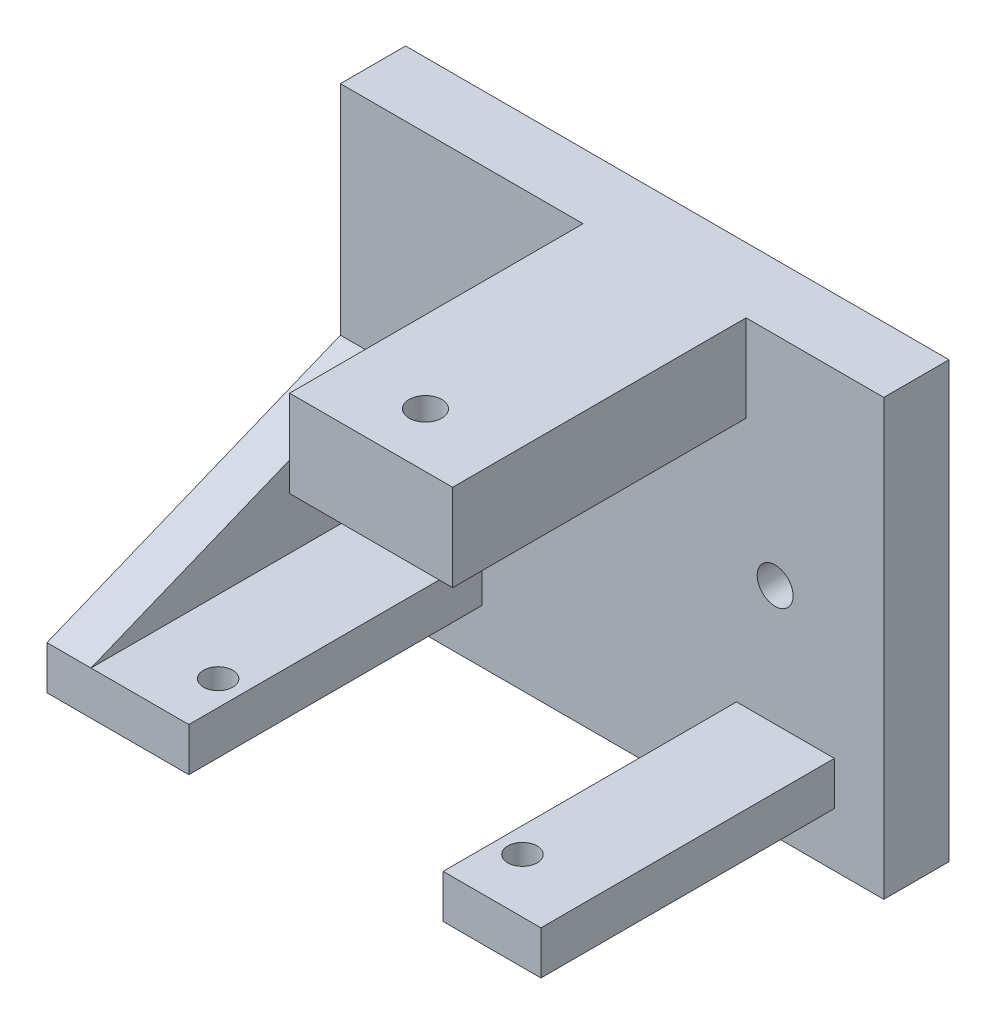
SolidWorks part; units mm, degrees
ref_plane "前视基准面" through (0, 0, 0) normal (0, 0, 1) x (1, 0, 0)
ref_plane "上视基准面" through (0, 0, 0) normal (0, 1, 0) x (1, 0, 0)
ref_plane "右视基准面" through (0, 0, 0) normal (1, 0, 0) x (0, 0, -1)
sketch "草图1" plane through (0, 0, 0) normal (0, 0, 1) x (1, 0, 0)
  line L0 (219.1261, 0) -> (249.1261, 0) construction
  line L2 (209.1261, 20) -> (259.1261, 20)
  line L3 (209.1261, 20) -> (209.1261, -20)
  line L4 (209.1261, -20) -> (259.1261, -20)
  line L5 (259.1261, 20) -> (259.1261, -20)
  line L6 (209.1261, 20) -> (259.1261, -20) construction
  line L7 (209.1261, -20) -> (259.1261, 20) construction
  circle A0 centre (219.1261, 0) radius 1.65
  circle A1 centre (249.1261, 0) radius 1.65
  point P4 (234.1261, 0)
  dimension "D4" = 3.3
  dimension "D1" = 10
  dimension "D2" = 50
  dimension "D3" = 40
extrude "凸台-拉伸1" add sketch "草图1" along normal blind 6
sketch "草图4" plane through (0, 0, 6) normal (0, 0, 1) x (1, 0, 0)
  line L0 (233.8761, 20) -> (233.8761, -20) construction
  line L3 (206.4014, -13.0416) -> (265.494, -13.0416) construction
  line L4 (222.6261, -15.0416) -> (217.7011, -15.0416) construction
  line L5 (213.1761, -11.0416) -> (222.1761, -11.0416)
  line L6 (213.1761, -11.0416) -> (213.1761, -15.0416)
  line L7 (213.1761, -15.0416) -> (222.1761, -15.0416)
  line L8 (222.1761, -11.0416) -> (222.1761, -15.0416)
  line L9 (213.1761, -11.0416) -> (222.1761, -15.0416) construction
  line L10 (213.1761, -15.0416) -> (222.1761, -11.0416) construction
  line L11 (254.5761, -15.0416) -> (245.5761, -11.0416) construction
  line L12 (254.5761, -11.0416) -> (245.5761, -15.0416) construction
  line L13 (245.5761, -11.0416) -> (245.5761, -15.0416)
  line L14 (254.5761, -15.0416) -> (245.5761, -15.0416)
  line L15 (254.5761, -11.0416) -> (254.5761, -15.0416)
  line L16 (254.5761, -11.0416) -> (245.5761, -11.0416)
  line L19 (259.1261, -20) -> (259.1261, 20) construction
  point P8 (217.6761, -13.0416)
  point P19 (250.0761, -13.0416)
  dimension "D1" = 4
  dimension "D2" = 9
  dimension "D3" = 11.7
  dimension "D4" = 25.25
extrude "凸台-拉伸2" add sketch "草图4" along normal blind 27
sketch "草图5" plane through (0, -15.0416, 0) normal (0, -1, 0) x (1, 0, 0)
  line L0 (222.1761, 19.5) -> (245.5761, 19.5) construction
  line L1 (222.1761, 33) -> (222.1761, 6) construction
  line L2 (245.5761, 33) -> (245.5761, 6) construction
  line L3 (233.8761, 19.5) -> (233.8761, 43.866) construction
  line L4 (209.1261, 6) -> (259.1261, 6) construction
  circle A0 centre (247.8761, 28) radius 1.35
  circle A1 centre (219.8761, 28) radius 1.35
  dimension "D3" = 2.7
  dimension "D1" = 14
  dimension "D2" = 22
extrude "切除-拉伸1" cut sketch "草图5" against normal blind 10
sketch "草图6" plane through (213.1761, 0, 0) normal (-1, 0, 0) x (0, 0, 1)
  line L0 (6, -15.0416) -> (6, -0.0416)
  line L1 (6, 20) -> (6, -20) construction
  line L2 (6, -0.0416) -> (33, -11.0416)
  line L3 (33, -11.0416) -> (33, -15.0416)
  line L4 (33, -15.0416) -> (6, -15.0416)
  dimension "D1" = 15
extrude "凸台-拉伸3" add sketch "草图6" along normal up to surface (4.05 mm away) up to face at (209.1261, 0, 3)
sketch "草图7" plane through (254.5761, 0, 0) normal (1, 0, 0) x (0, 0, -1)
  line L0 (-6, -15.0416) -> (-6, -0.0416)
  line L1 (-6, -20) -> (-6, 20) construction
  line L2 (-6, -0.0416) -> (-33, -11.0416)
  line L3 (-33, -11.0416) -> (-33, -15.0416)
  line L4 (-33, -15.0416) -> (-6, -15.0416)
  point P5 (0, 0)
  dimension "D1" = 15
sketch "草图8" plane through (0, 20, 0) normal (0, 1, 0) x (1, 0, 0)
  line L0 (238.9511, -6) -> (238.9511, -53.7115) construction
  line L1 (259.1261, -6) -> (209.1261, -6) construction
  line L4 (246.4511, -33) -> (231.4511, -33)
  line L5 (246.4511, -33) -> (246.4511, -6)
  line L6 (246.4511, -6) -> (231.4511, -6)
  line L7 (231.4511, -33) -> (231.4511, -6)
  line L8 (246.4511, -33) -> (231.4511, -6) construction
  line L9 (246.4511, -6) -> (231.4511, -33) construction
  circle A0 centre (238.9511, -28) radius 1.5
  point P6 (238.9511, -19.5)
  point P14 (0, 0)
  dimension "D2" = 3
  dimension "D1" = 27
  dimension "D3" = 15
extrude "凸台-拉伸5" add sketch "草图8" against normal blind 8
